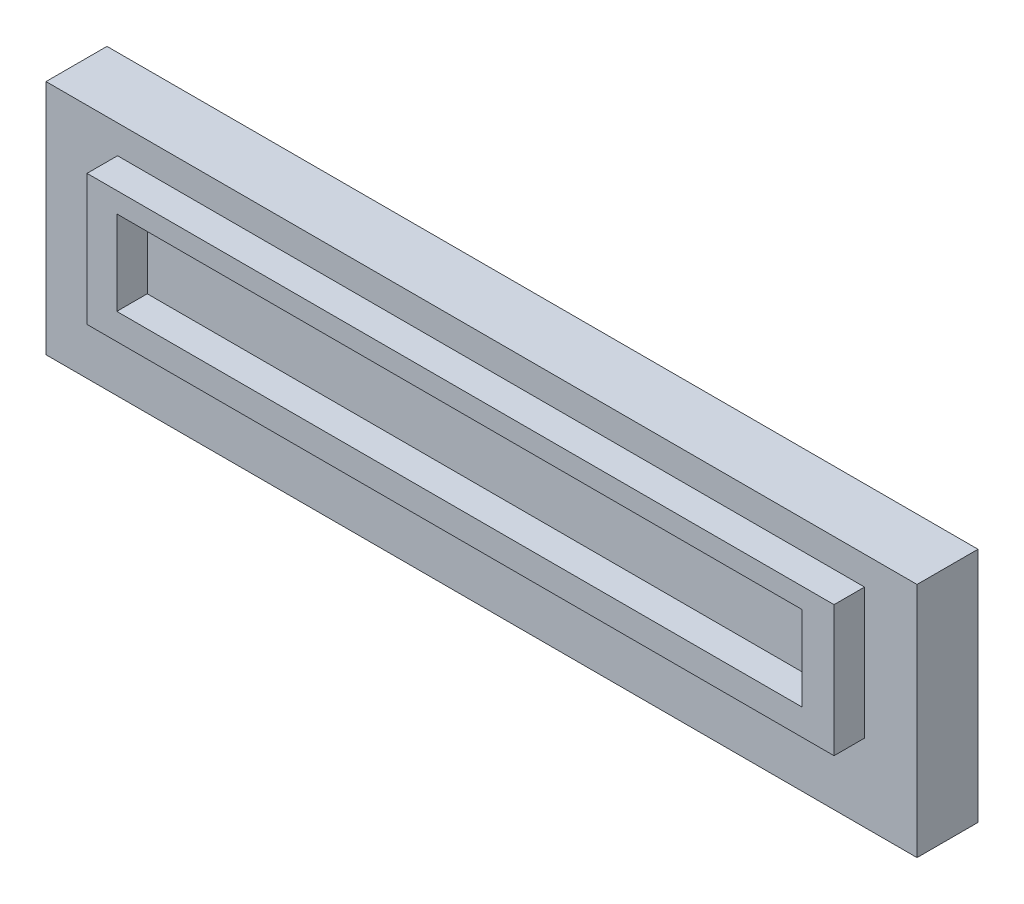
SolidWorks part; units mm, degrees
ref_plane "Front Plane" through (0, 0, 0) normal (0, 0, 1) x (1, 0, 0)
ref_plane "Top Plane" through (0, 0, 0) normal (0, 1, 0) x (1, 0, 0)
ref_plane "Right Plane" through (0, 0, 0) normal (1, 0, 0) x (0, 0, -1)
sketch "Sketch1" plane through (0, 0, 0) normal (0, 0, 1) x (1, 0, 0)
  line L1 (57.3478, 20.4323) -> (-85.5067, 20.4323)
  line L2 (57.3478, 20.4323) -> (57.3478, -18.3719)
  line L3 (57.3478, -18.3719) -> (-85.5067, -18.3719)
  line L4 (-85.5067, 20.4323) -> (-85.5067, -18.3719)
extrude "Boss-Extrude1" add sketch "Sketch1" along normal blind 10
sketch "Sketch2" plane through (0, 0, 10) normal (0, 0, 1) x (1, 0, 0)
  line L1 (48.7382, 15.7592) -> (-73.7756, 15.7592)
  line L2 (48.7382, 15.7592) -> (48.7382, -5.7003)
  line L3 (48.7382, -5.7003) -> (-73.7756, -5.7003)
  line L4 (-73.7756, 15.7592) -> (-73.7756, -5.7003)
  line L5 (43.4709, 12.4427) -> (-68.8985, 12.4427)
  line L6 (43.4709, 12.4427) -> (43.4709, -1.4084)
  line L7 (43.4709, -1.4084) -> (-68.8985, -1.4084)
  line L8 (-68.8985, 12.4427) -> (-68.8985, -1.4084)
extrude "Boss-Extrude2" add sketch "Sketch2" along normal blind 5
